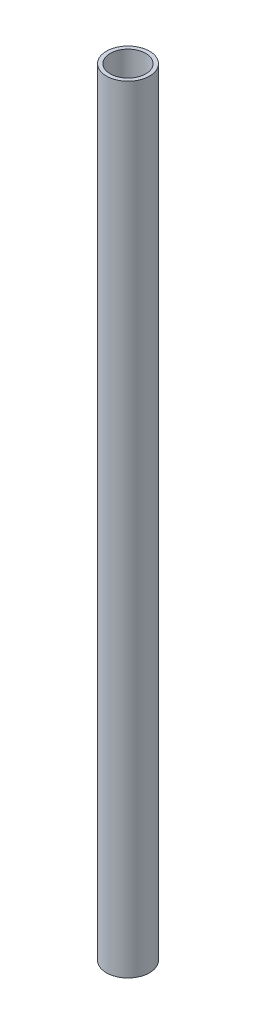
SolidWorks part; units mm, degrees
ref_plane "Front Plane" through (0, 0, 0) normal (0, 0, 1) x (1, 0, 0)
ref_plane "Top Plane" through (0, 0, 0) normal (0, 1, 0) x (1, 0, 0)
ref_plane "Right Plane" through (0, 0, 0) normal (1, 0, 0) x (0, 0, -1)
sketch "Sketch1" plane through (0, 0, 0) normal (0, 1, 0) x (1, 0, 0)
  circle A0 centre (0, 0) radius 12.7
  circle A1 centre (0, 0) radius 10.4648
  dimension "D1" = 25.4
  dimension "D2" = 20.9296
extrude "Boss-Extrude1" add sketch "Sketch1" along normal blind 457.2
